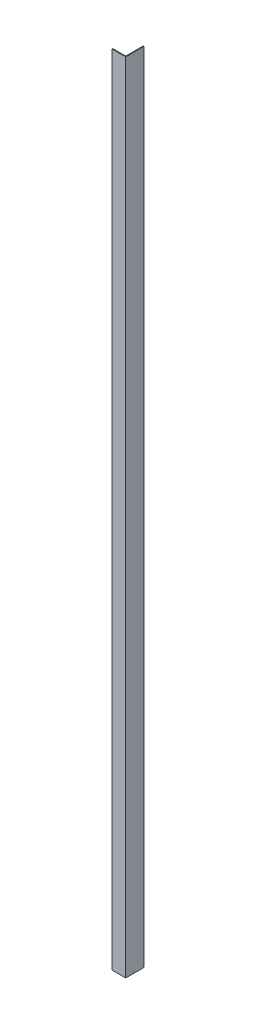
SolidWorks part; units mm, degrees
ref_plane "Front Plane" through (0, 0, 0) normal (0, 0, 1) x (1, 0, 0)
ref_plane "Top Plane" through (0, 0, 0) normal (0, 1, 0) x (1, 0, 0)
ref_plane "Right Plane" through (0, 0, 0) normal (1, 0, 0) x (0, 0, -1)
other "Configuration Table"
sketch "Sketch1" plane through (0, 0, 0) normal (0, 1, 0) x (1, 0, 0)
  line L0 (0, -40) -> (0, -38.5)
  line L1 (0, -38.5) -> (28.5, -38.5)
  line L2 (28.5, -38.5) -> (28.5, 0)
  line L3 (28.5, 0) -> (30, 0)
  line L4 (30, 0) -> (30, -40)
  line L5 (30, -40) -> (0, -40)
extrude "TOPPING_sove_sol_1" add sketch "Sketch1" along normal blind 1770 from offset 200 separate body
